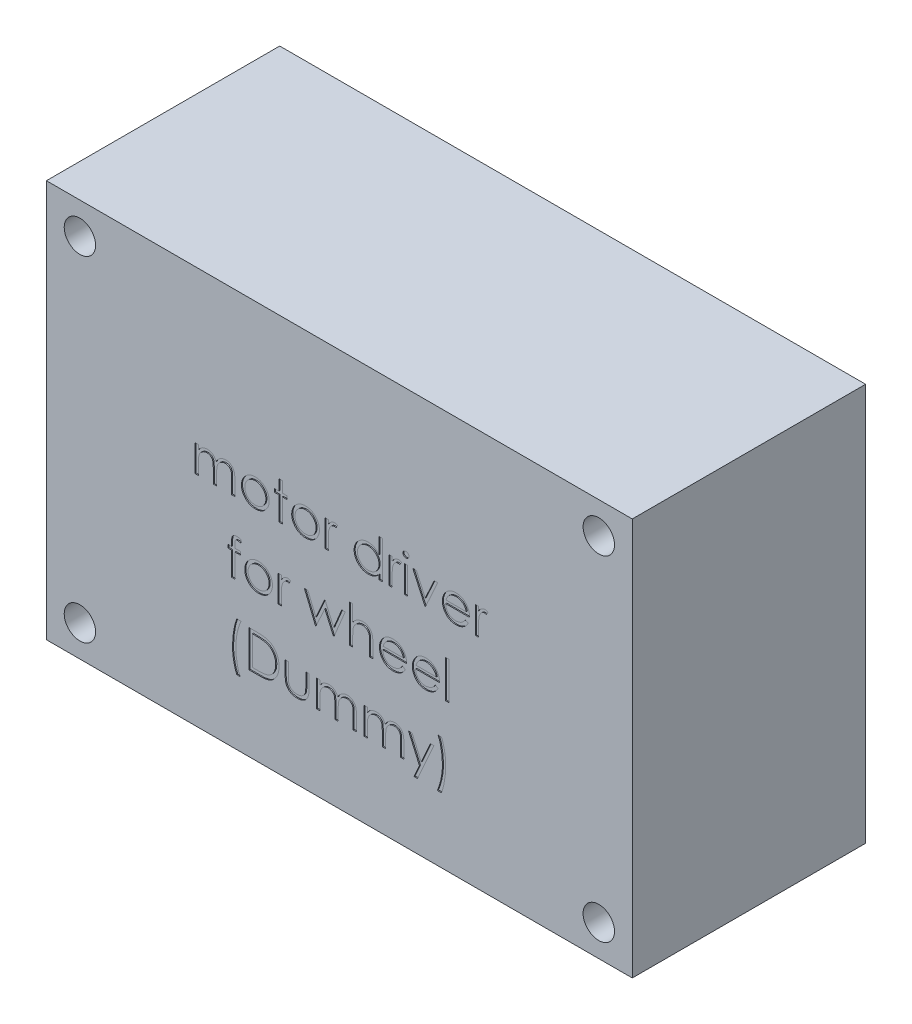
SolidWorks part; units mm, degrees
ref_plane "정면" through (0, 0, 0) normal (0, 0, 1) x (1, 0, 0)
ref_plane "윗면" through (0, 0, 0) normal (0, 1, 0) x (1, 0, 0)
ref_plane "우측면" through (0, 0, 0) normal (1, 0, 0) x (0, 0, -1)
sketch "스케치1" plane through (0, 0, 0) normal (0, 0, 1) x (1, 0, 0)
  line L1 (-28, 19) -> (28, 19)
  line L2 (-28, 19) -> (-28, -19)
  line L3 (-28, -19) -> (28, -19)
  line L4 (28, 19) -> (28, -19)
  line L5 (-28, 19) -> (28, -19) construction
  line L6 (-28, -19) -> (28, 19) construction
  point P0 (0, 0)
  dimension "D1" = 56
  dimension "D2" = 38
extrude "보스-돌출1" add sketch "스케치1" along normal blind 22.3
sketch "스케치2" plane through (0, 0, 0) normal (0, 0, -1) x (-1, 0, 0)
  line L0 (-28, 19) -> (28, 19) construction
  line L1 (28, -19) -> (-28, -19) construction
  line L2 (28, 19) -> (28, -19) construction
  line L3 (-28, -19) -> (-28, 19) construction
  circle A0 centre (-24.8, 16) radius 1.5
  circle A1 centre (24.8, 16) radius 1.5
  circle A2 centre (24.8, -16) radius 1.5
  circle A3 centre (-24.8, -16) radius 1.5
  dimension "D1" = 3
  dimension "D2" = 3
  dimension "D3" = 3
  dimension "D4" = 3
  dimension "D5" = 3
  dimension "D6" = 3
  dimension "D7" = 3
  dimension "D8" = 3
  dimension "D9" = 3.2
  dimension "D10" = 3.2
  dimension "D11" = 3.2
  dimension "D12" = 3.2
extrude "컷-돌출1" cut sketch "스케치2" against normal blind 22.3
sketch "스케치3" plane through (0, 0, 22.3) normal (0, 0, 1) x (1, 0, 0)
  line L0 (-28, 1.8597) -> (28, 1.8597) construction
  line L1 (-28, 19) -> (-28, -19) construction
  line L2 (28, -19) -> (28, 19) construction
  text T0 "motor driver\r\nfor wheel\r\n(Dummy)\r\n"
extrude "컷-돌출2" cut sketch "스케치3" against normal blind 0.1
